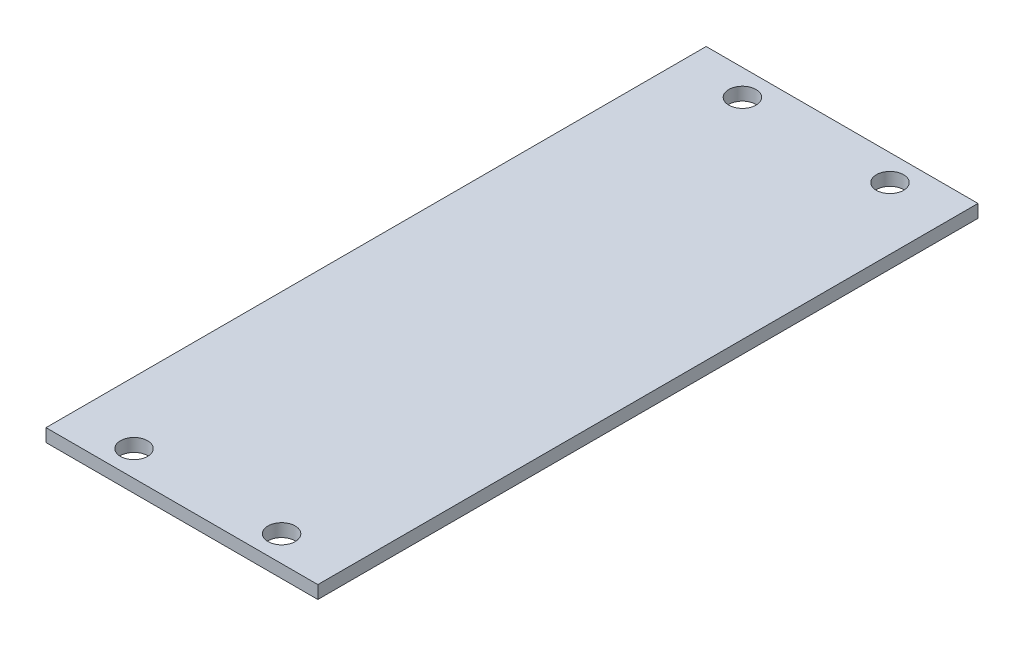
SolidWorks part; units mm, degrees
ref_plane "Front Plane" through (0, 0, 0) normal (0, 0, 1) x (1, 0, 0)
ref_plane "Top Plane" through (0, 0, 0) normal (0, 1, 0) x (1, 0, 0)
ref_plane "Right Plane" through (0, 0, 0) normal (1, 0, 0) x (0, 0, -1)
sketch "Sketch1" plane through (0, 0, 0) normal (0, 1, 0) x (1, 0, 0)
  line L1 (-10.5, -25.5) -> (10.5, -25.5)
  line L2 (-10.5, -25.5) -> (-10.5, 25.5)
  line L3 (-10.5, 25.5) -> (10.5, 25.5)
  line L4 (10.5, -25.5) -> (10.5, 25.5)
  line L5 (-10.5, -25.5) -> (10.5, 25.5) construction
  line L6 (-10.5, 25.5) -> (10.5, -25.5) construction
  point P0 (0, 0)
  dimension "D1" = 51
  dimension "D2" = 21
extrude "Boss-Extrude1" add sketch "Sketch1" along normal blind 1
sketch "Sketch3" plane through (0, 1, 0) normal (0, 1, 0) x (1, 0, 0)
  line L0 (10.5, 25.5) -> (-10.5, 25.5) construction
  line L1 (-5.7, -23.5) -> (5.7, -23.5) construction
  line L2 (-5.7, -23.5) -> (-5.7, 23.5) construction
  line L3 (-5.7, 23.5) -> (5.7, 23.5) construction
  line L4 (5.7, -23.5) -> (5.7, 23.5) construction
  line L5 (-5.7, -23.5) -> (5.7, 23.5) construction
  line L6 (-5.7, 23.5) -> (5.7, -23.5) construction
  circle A0 centre (-5.7, 23.5) radius 1.05
  point P0 (0, 0)
  dimension "D3" = 2.1
  dimension "D1" = 2
  dimension "D2" = 11.4
extrude "Cut-Extrude2" cut sketch "Sketch3" against normal through all
mirror "Mirror1" about plane through (0, 0, 0) normal (1, 0, 0) of "Cut-Extrude2"
mirror "Mirror2" about plane through (0, 0, 0) normal (0, 0, 1) of "Mirror1", "Cut-Extrude2"
